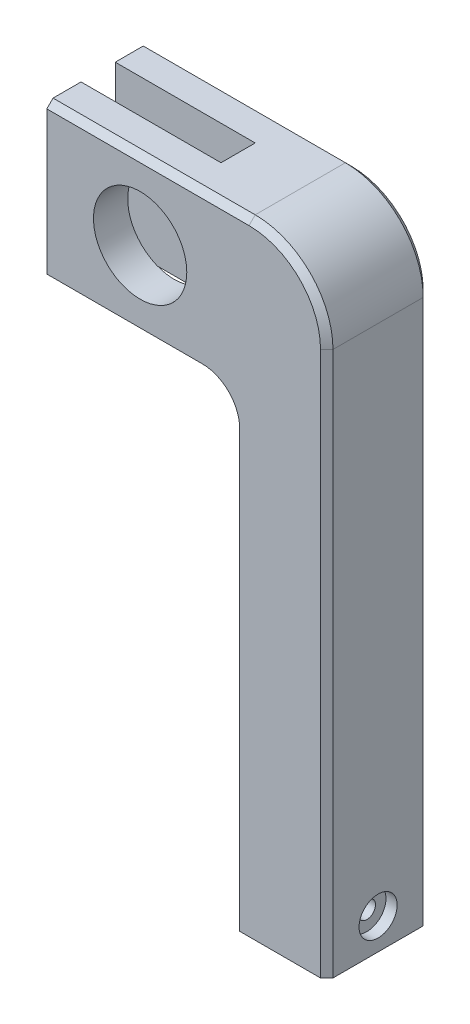
SolidWorks part; units mm, degrees
ref_plane "Front Plane" through (0, 0, 0) normal (0, 0, 1) x (1, 0, 0)
ref_plane "Top Plane" through (0, 0, 0) normal (0, 1, 0) x (1, 0, 0)
ref_plane "Right Plane" through (0, 0, 0) normal (1, 0, 0) x (0, 0, -1)
sketch "Sketch1" plane through (0, 0, 0) normal (0, 0, 1) x (1, 0, 0)
  line L0 (0, 0) -> (-30, 0)
  line L9 (-30, 150) -> (-30, 0)
  line L10 (-30, 150) -> (-90, 150)
  line L11 (-90, 150) -> (-90, 200)
  line L12 (-90, 200) -> (0, 200)
  line L13 (0, 200) -> (0, 0)
  dimension "D1" = 200
  dimension "D2" = 90
  dimension "D3" = 30
  dimension "D4" = 50
extrude "Boss-Extrude1" add sketch "Sketch1" against normal mid plane 33
sketch "Sketch3" plane through (0, 200, 0) normal (0, 1, 0) x (1, 0, 0)
  line L0 (-90, 16.5) -> (-90, -16.5) construction
  line L1 (-45, -5.5) -> (-90, -5.5)
  line L2 (-45, -5.5) -> (-45, 5.5)
  line L3 (-45, 5.5) -> (-90, 5.5)
  line L4 (-90, -5.5) -> (-90, 5.5)
  line L5 (-45, -5.5) -> (-90, 5.5) construction
  line L6 (-45, 5.5) -> (-90, -5.5) construction
  line L7 (-90, 0) -> (0, 0) construction
  point P0 (-67.5, 0)
  point P10 (-75.0004, 0)
  dimension "D1" = 11
  dimension "D2" = 45
extrude "Cut-Extrude1" cut sketch "Sketch3" against normal up to next
fillet "Fillet1" radius 25 1 edges at (0, 200, 0)
fillet "Fillet2" radius 10 1 edges at (-30, 150, 0)
sketch "Sketch4" plane through (0, 0, 16.5) normal (0, 0, 1) x (1, 0, 0)
  line L0 (-90, 200) -> (-90, 150) construction
  line L1 (-90, 175) -> (-39.4804, 175) construction
  circle A0 centre (-60, 175) radius 15
  point P6 (0, 0)
  dimension "D2" = 30
  dimension "D1" = 30
extrude "Cut-Extrude2" cut sketch "Sketch4" against normal up to next
sketch "Sketch5" plane through (0, 0, -16.5) normal (0, 0, -1) x (-1, 0, 0)
  line L0 (90, 175) -> (42.6224, 175) construction
  line L1 (90, 200) -> (90, 150) construction
  circle A0 centre (60, 175) radius 9.75
  point P6 (69.5329, 175)
  dimension "D1" = 30
  dimension "D2" = 19.5
extrude "Cut-Extrude3" cut sketch "Sketch5" against normal up to next
hole_wizard "Ø3.0mm Dowel Hole1" positions "3DSketch1" profile "Sketch6" hole size "Ø3.0" standard "ANSI Metric"
sketch3d "3DSketch1"
  line L1 (-90, 150, -16.5) -> (-90, 150, -5.5) construction
  line L2 (-90, 200, -16.5) -> (-90, 150, -16.5) construction
  line L3 (-90, 200, -16.5) -> (-90, 200, -5.5) construction
  line L4 (-90, 150, 5.5) -> (-90, 150, 16.5) construction
  line L5 (-90, 200, 16.5) -> (-90, 150, 16.5) construction
  line L6 (-90, 200, 5.5) -> (-90, 200, 16.5) construction
  point P0 (-90, 195, -11)
  point P2 (-90, 155, -11)
  point P4 (-90, 195, 11)
  point P6 (-90, 155, 11)
  dimension "D1" = 40
  dimension "D2" = 5
  dimension "D3" = 5.5
  dimension "D4" = 5.5
  dimension "D5" = 5
  dimension "D6" = 40
  dimension "D7" = 5
  dimension "D8" = 5.5
  dimension "D9" = 5
  dimension "D10" = 5.5
sketch "Sketch6" plane through (-90, 195, -11) normal (0, 1, 0) x (0, 0, 1)
  line L0 (0, 0) -> (0, 20)
  line L1 (0, 20) -> (1.5, 19.0987)
  line L2 (1.5, 19.0987) -> (1.5, 0)
  line L5 (1.5, 0) -> (0, 0)
  line L10 (0, 20) -> (-1.5, 19.0987) construction
  line L11 (0, -6.35) -> (0, 107.95) construction
  dimension "Hole Dia." = 3
  dimension "Hole Depth" = 20
  dimension "Drill Angle" = 118
chamfer "Chamfer1" distance 2 angle 45 12 edges at (-65, 150, 16.5) (-32.9289, 147.0711, 16.5) (-30, 70, 16.5) (-65, 150, -16.5) (-32.9289, 147.0711, -16.5) (-30, 70, -16.5) (-57.5, 200, -16.5) (-7.3223, 192.6777, -16.5) (0, 87.5, -16.5) (-57.5, 200, 16.5) (-7.3223, 192.6777, 16.5) (0, 87.5, 16.5)
sketch "Sketch9" plane through (0, 0, 0) normal (1, 0, 0) x (0, 0, -1)
  line L0 (0, 0) -> (0, 10) construction
  line L1 (14.5, 0) -> (-14.5, 0) construction
  point P1 (0, 10)
  dimension "D1" = 10
hole_wizard "CBORE for M5 Hex Head Bolt1" positions "Sketch9" profile "Sketch10" counterbore size "M5" standard "ANSI Metric" end condition up to next
sketch "Sketch10" plane through (0, 10, 0) normal (0, 1, 0) x (0, 0, -1)
  line L0 (0, 0) -> (0, 30)
  line L1 (0, 30) -> (2.75, 30)
  line L3 (2.75, 30) -> (2.75, 3.58)
  line L4 (2.75, 3.58) -> (6.12, 3.58)
  line L5 (6.12, 3.58) -> (6.12, 0)
  line L7 (6.12, 0) -> (0, 0)
  line L11 (0, -6.35) -> (0, 107.95) construction
  dimension "Thru Hole Dia." = 5.5
  dimension "Thru Hole Depth" = 30
  dimension "C'Bore Dia." = 12.24
  dimension "C'Bore Depth" = 3.58
